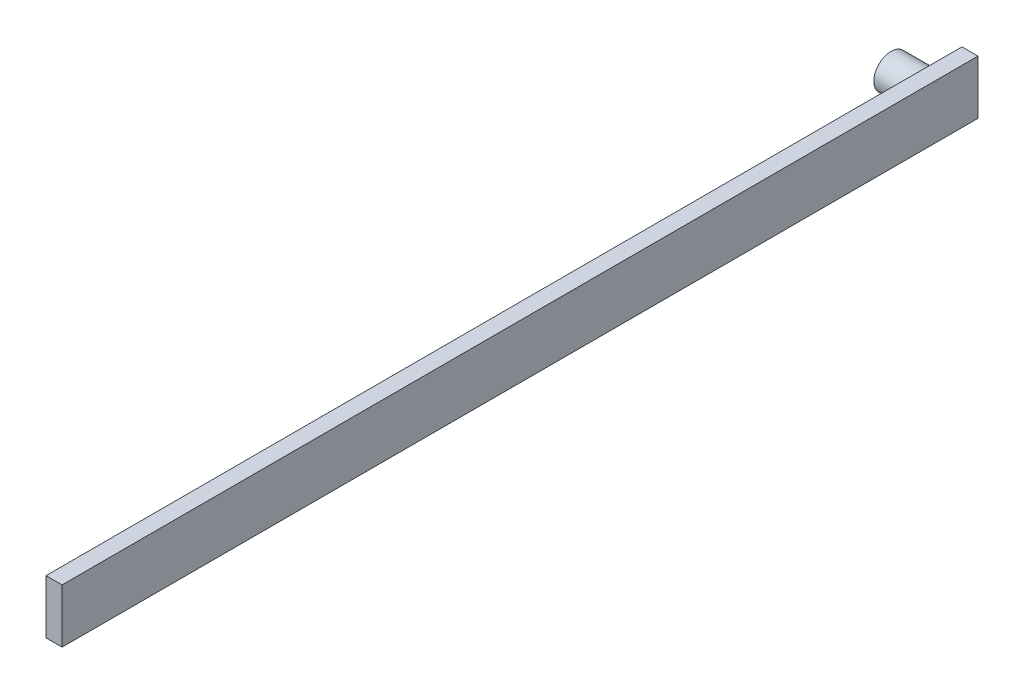
SolidWorks part; units mm, degrees
ref_plane "Front Plane" through (0, 0, 0) normal (0, 0, 1) x (1, 0, 0)
ref_plane "Top Plane" through (0, 0, 0) normal (0, 1, 0) x (1, 0, 0)
ref_plane "Right Plane" through (0, 0, 0) normal (1, 0, 0) x (0, 0, -1)
sketch "Sketch1" plane through (0, 0, 0) normal (1, 0, 0) x (0, 0, -1)
  circle A0 centre (0, 0) radius 7.5
  dimension "D1" = 15
extrude "Boss-Extrude1" add sketch "Sketch1" along normal blind 18
sketch "Sketch2" plane through (18, 0, 0) normal (1, 0, 0) x (0, 0, -1)
  line L0 (12.9555, 11.7589) -> (-386.5877, 11.7589)
  line L4 (12.9555, 11.7589) -> (12.9555, -11.7589)
  line L5 (-386.5877, 11.7589) -> (-386.5877, -11.7589)
  line L6 (-386.5877, -11.7589) -> (12.9555, -11.7589)
  point P0 (0, 0)
  point P2 (12.9555, 0)
  dimension "D1" = 23.5178
  dimension "D2" = 399.5432
  dimension "D3" = 12.9555
  dimension "D4" = 11.7589
extrude "Boss-Extrude2" add sketch "Sketch2" along normal blind 7
